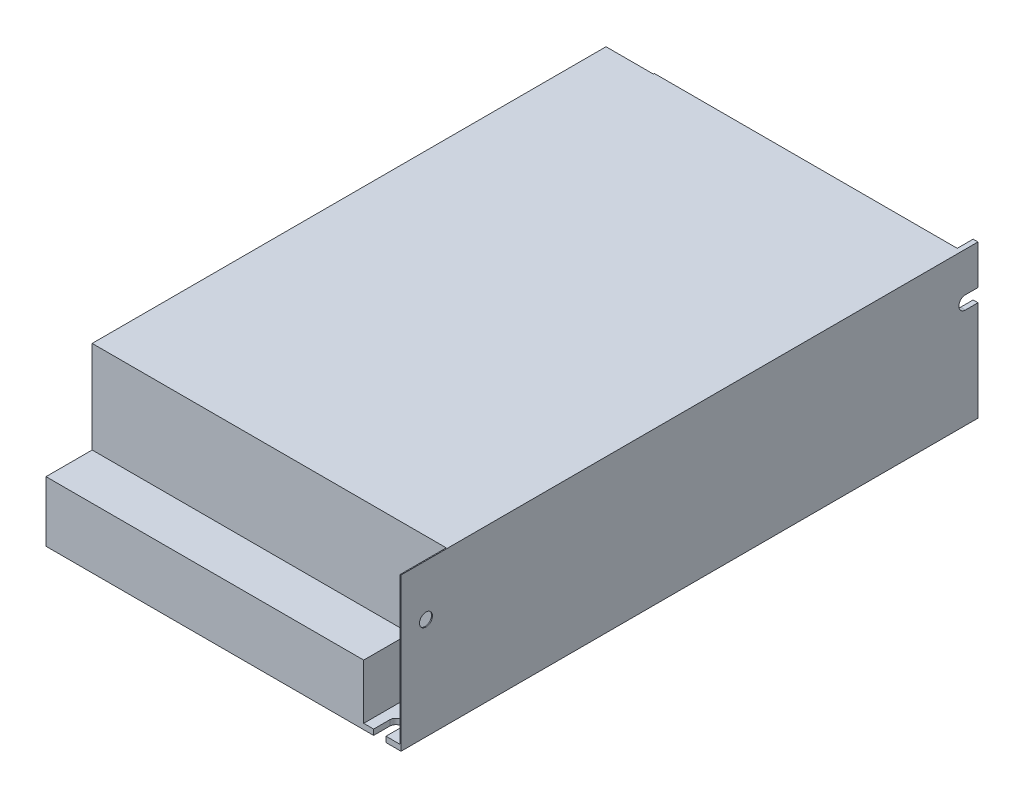
SolidWorks part; units mm, degrees
ref_plane "Front Plane" through (0, 0, 0) normal (0, 0, 1) x (1, 0, 0)
ref_plane "Top Plane" through (0, 0, 0) normal (0, 1, 0) x (1, 0, 0)
ref_plane "Right Plane" through (0, 0, 0) normal (1, 0, 0) x (0, 0, -1)
sketch "Sketch1" plane through (0, 0, 0) normal (0, 1, 0) x (1, 0, 0)
  line L1 (0, 0) -> (97.6884, 0)
  line L2 (0, 0) -> (0, 158.75)
  line L3 (0, 158.75) -> (97.6884, 158.75)
  line L4 (97.6884, 0) -> (97.6884, 158.75)
  dimension "D1" = 97.6884
  dimension "D2" = 158.75
extrude "Boss-Extrude1" add sketch "Sketch1" along normal blind 42
sketch "Sketch2" plane through (97.6884, 0, 0) normal (1, 0, 0) x (0, 0, -1)
  line L0 (0, 42) -> (0, 0) construction
  line L1 (0, 42) -> (12.7, 42)
  line L2 (0, 42) -> (0, 16.6)
  line L3 (0, 16.6) -> (12.7, 16.6)
  line L4 (12.7, 42) -> (12.7, 16.6)
  line L5 (0, 42) -> (158.75, 42) construction
  dimension "D1" = 12.7
  dimension "D2" = 25.4
extrude "Cut-Extrude1" cut sketch "Sketch2" along normal offset from surface (97.4344 mm away) 0.254 from surface at -97.6884 up to face at (97.6884, 21, -79.375) starting at face at (0, 21, -79.375)
sketch "Sketch3" plane through (0, 16.6, 0) normal (0, 1, 0) x (1, 0, 0)
  line L1 (97.4344, 0) -> (87.4141, 0)
  line L2 (97.4344, 0) -> (97.4344, 10.1346)
  line L3 (97.4344, 10.1346) -> (87.4141, 10.1346)
  line L4 (87.4141, 0) -> (87.4141, 10.1346)
  dimension "D1" = 10.0203
  dimension "D2" = 10.1346
extrude "Cut-Extrude2" cut sketch "Sketch3" against normal offset from surface (15.076 mm away) 1.524 up to face at (48.8442, 0, -79.375)
sketch "Sketch4" plane through (0, 42, 0) normal (0, 1, 0) x (1, 0, 0)
  line L0 (0, 158.75) -> (0, 12.7) construction
  line L1 (0, 158.75) -> (13.0175, 158.75)
  line L2 (0, 158.75) -> (0, 154.0891)
  line L3 (0, 154.0891) -> (13.0175, 154.0891)
  line L4 (13.0175, 158.75) -> (13.0175, 154.0891)
  line L5 (97.6884, 158.75) -> (0, 158.75) construction
  dimension "D1" = 4.6609
  dimension "D2" = 13.0175
extrude "Cut-Extrude3" cut sketch "Sketch4" against normal offset from surface (40.476 mm away) 1.524 up to face at (48.8442, 0, -79.375)
sketch "Sketch5" plane through (0, 1.524, 0) normal (0, 1, 0) x (1, 0, 0)
  line L0 (0, 158.75) -> (0, 154.0891) construction
  line L1 (13.0175, 158.75) -> (0.508, 158.75)
  line L2 (13.0175, 158.75) -> (13.0175, 151.13)
  line L3 (13.0175, 151.13) -> (0.508, 151.13)
  line L4 (0.508, 158.75) -> (0.508, 151.13)
  dimension "D1" = 0.508
  dimension "D2" = 7.62
extrude "Cut-Extrude4" cut sketch "Sketch5" along normal blind 7.62
sketch "Sketch6" plane through (0, 42, 0) normal (0, 1, 0) x (1, 0, 0)
  line L0 (97.6884, 158.75) -> (13.0175, 158.75) construction
  line L1 (96.3549, 158.75) -> (0, 158.75)
  line L2 (96.3549, 158.75) -> (96.3549, 154.3685)
  line L3 (96.3549, 154.3685) -> (0, 154.3685)
  line L4 (0, 158.75) -> (0, 154.3685)
  line L5 (97.6884, 0) -> (97.6884, 158.75) construction
  dimension "D1" = 1.3335
  dimension "D2" = 4.3815
extrude "Cut-Extrude5" cut sketch "Sketch6" against normal blind 30.2133
sketch "Sketch7" plane through (0, 1.524, 0) normal (0, 1, 0) x (1, 0, 0)
  line L0 (5.08, 158.75) -> (5.08, 154.813)
  line L1 (13.0175, 158.75) -> (0, 158.75) construction
  line L2 (8.255, 154.813) -> (8.255, 158.75)
  line L3 (8.255, 158.75) -> (5.08, 158.75)
  line L4 (0, 158.75) -> (0, 154.0891) construction
  arc A0 (5.08, 154.813) -> (8.255, 154.813) centre (6.6675, 154.813) ccw
  dimension "D2" = 3.175
  dimension "D1" = 5.08
  dimension "D3" = 3.937
extrude "Cut-Extrude6" cut sketch "Sketch7" against normal through all
sketch "Sketch8" plane through (97.6884, 0, 0) normal (1, 0, 0) x (0, 0, -1)
  line L0 (158.75, 31.1288) -> (155.2829, 31.1288)
  line L1 (158.75, 42) -> (158.75, 0) construction
  line L2 (155.2829, 27.5093) -> (158.75, 27.5093)
  line L3 (158.75, 27.5093) -> (158.75, 31.1288)
  line L4 (0, 42) -> (158.75, 42) construction
  arc A0 (155.2829, 31.1288) -> (155.2829, 27.5093) centre (155.2829, 29.3191) ccw
  dimension "D1" = 10.8712
  dimension "D2" = 3.6195
  dimension "D3" = 3.4671
extrude "Cut-Extrude7" cut sketch "Sketch8" against normal up to surface (1.3335 mm away) up to face at (96.3549, 26.8934, -156.5592)
sketch "Sketch9" plane through (97.6884, 0, 0) normal (1, 0, 0) x (0, 0, -1)
  line L0 (0, 42) -> (158.75, 42) construction
  line L1 (0, 42) -> (0, 0) construction
  circle A0 centre (6.858, 27.9665) radius 1.778
  dimension "D1" = 3.556
  dimension "D2" = 14.0335
  dimension "D3" = 6.858
extrude "Cut-Extrude8" cut sketch "Sketch9" against normal up to surface (0.254 mm away) up to face at (97.4344, 20.0413, -7.6115)
sketch "Sketch10" plane through (0, 0, 0) normal (0, -1, 0) x (1, 0, 0)
  line L0 (93.5482, 0) -> (90.1446, 0)
  line L1 (0, 0) -> (97.6884, 0) construction
  line L2 (90.1446, 0) -> (90.1446, -4.445)
  line L3 (93.5482, -4.445) -> (93.5482, 0)
  line L4 (97.6884, 0) -> (97.6884, -158.75) construction
  arc A0 (90.1446, -4.445) -> (93.5482, -4.445) centre (91.8464, -4.445) ccw
  dimension "D1" = 3.4036
  dimension "D2" = 4.1402
  dimension "D3" = 4.445
extrude "Cut-Extrude9" cut sketch "Sketch10" against normal up to surface (1.524 mm away) up to face at (92.4242, 1.524, -5.0673)
